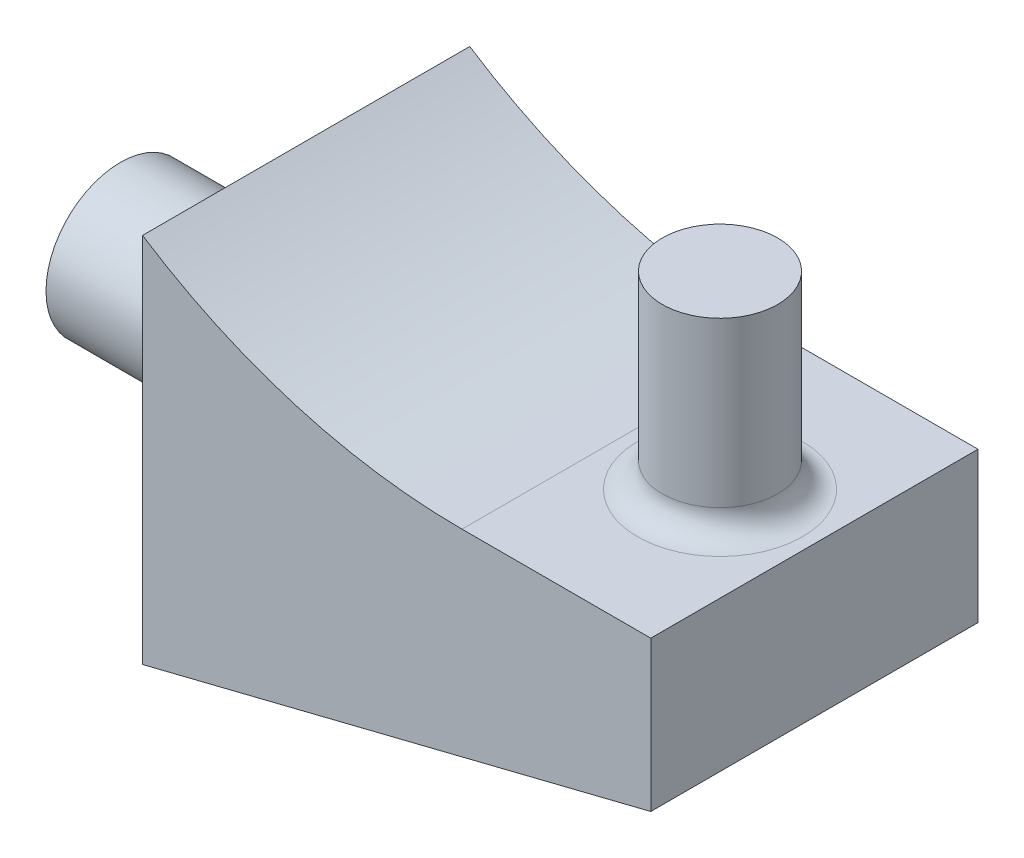
SolidWorks part; units mm, degrees
material "AISI 4340 Steel, normalized"
ref_plane "Front Plane" through (0, 0, 0) normal (0, 0, 1) x (1, 0, 0)
ref_plane "Top Plane" through (0, 0, 0) normal (0, 1, 0) x (1, 0, 0)
ref_plane "Right Plane" through (0, 0, 0) normal (1, 0, 0) x (0, 0, -1)
sketch "Sketch4" plane through (0, 0, 0) normal (0, 0, 1) x (1, 0, 0)
  line L0 (253.4053, 274.9854) -> (253.4053, 244.9854)
  line L1 (253.4053, 244.9854) -> (294.4367, 255.2217)
  line L2 (294.4367, 255.2217) -> (294.4367, 267.3435)
  line L3 (294.4367, 267.3435) -> (279.1967, 267.3435)
  arc A0 (279.1967, 267.3435) -> (253.4053, 274.9854) centre (279.1967, 314.6873) cw
  dimension "D3" = 47.3438
  dimension "D1" = 30
  dimension "D2" = 41.0314
  dimension "D4" = 12.1218
  dimension "D5" = 15.24
extrude "Boss-Extrude1" add sketch "Sketch4" along normal blind 26.416
sketch "Sketch5" plane through (0, 267.3435, 0) normal (0, 1, 0) x (1, 0, 0)
  line L0 (294.4367, -13.208) -> (279.1967, -13.208) construction
  line L1 (294.4367, -26.416) -> (294.4367, 0) construction
  line L2 (279.1967, -26.416) -> (279.1967, 0) construction
  circle A0 centre (286.8167, -13.208) radius 4.6566
  dimension "D1" = 9.3131
extrude "Boss-Extrude2" add sketch "Sketch5" along normal blind 15.24
sketch "Sketch6" plane through (253.4053, 0, 0) normal (-1, 0, 0) x (0, 0, 1)
  line L5 (26.416, 259.9854) -> (0, 259.9854) construction
  circle A0 centre (13.208, 259.9854) radius 6
  dimension "D1" = 12
extrude "Boss-Extrude3" add sketch "Sketch6" along normal blind 15
fillet "Fillet1" radius 2 1 edges at (253.4053, 259.9854, 19.208)
fillet "Fillet2" radius 2 1 edges at (286.8167, 267.3435, 8.5514)
